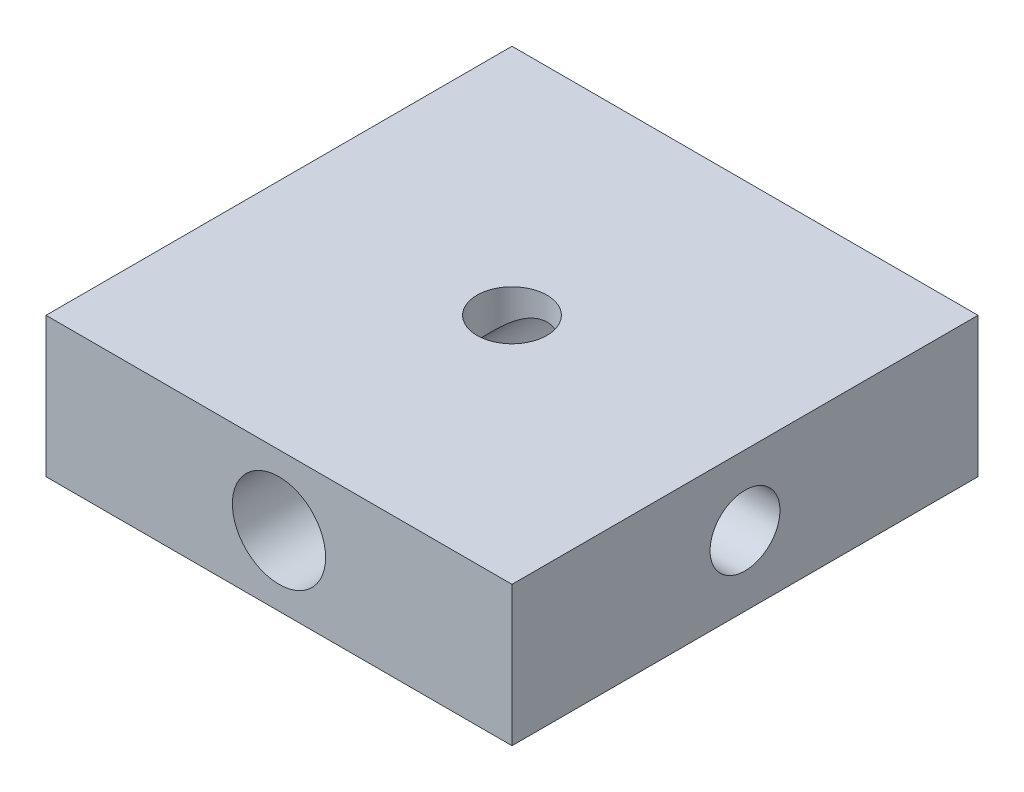
SolidWorks part; units mm, degrees
ref_plane "Front Plane" through (0, 0, 0) normal (0, 0, 1) x (1, 0, 0)
ref_plane "Top Plane" through (0, 0, 0) normal (0, 1, 0) x (1, 0, 0)
ref_plane "Right Plane" through (0, 0, 0) normal (1, 0, 0) x (0, 0, -1)
sketch "Sketch1" plane through (0, 0, 0) normal (0, 1, 0) x (1, 0, 0)
  line L1 (-10, -10) -> (10, -10)
  line L2 (-10, -10) -> (-10, 10)
  line L3 (-10, 10) -> (10, 10)
  line L4 (10, -10) -> (10, 10)
  line L5 (-10, -10) -> (10, 10) construction
  line L6 (-10, 10) -> (10, -10) construction
  point P0 (0, 0)
  dimension "D1" = 20
  dimension "D2" = 20
extrude "Boss-Extrude1" add sketch "Sketch1" along normal blind 6
sketch "Sketch2" plane through (0, 0, 10) normal (0, 0, 1) x (1, 0, 0)
  line L0 (-10, 3) -> (10, 3) construction
  line L1 (-10, 6) -> (-10, 0) construction
  line L2 (10, 6) -> (10, 0) construction
  line L3 (0, 6) -> (0, 0) construction
  line L4 (-10, 6) -> (10, 6) construction
  line L5 (-10, 0) -> (10, 0) construction
  circle A0 centre (0, 3) radius 2
  dimension "D1" = 4
extrude "Cut-Extrude1" cut sketch "Sketch2" against normal blind 20
sketch "Sketch3" plane through (0, 6, 0) normal (0, 1, 0) x (1, 0, 0)
  circle A0 centre (0, 0) radius 1.5
  dimension "D1" = 3
extrude "Cut-Extrude2" cut sketch "Sketch3" against normal blind 3
sketch "Sketch4" plane through (10, 0, 0) normal (1, 0, 0) x (0, 0, -1)
  line L0 (-10, 3) -> (10, 3) construction
  line L1 (-10, 6) -> (-10, 0) construction
  line L2 (10, 6) -> (10, 0) construction
  line L3 (0, 6) -> (0, 0) construction
  line L4 (-10, 6) -> (10, 6) construction
  circle A0 centre (0, 3) radius 1.5
  dimension "D1" = 3
extrude "Cut-Extrude3" cut sketch "Sketch4" against normal blind 9
sketch "Sketch5" plane through (-10, 0, 0) normal (-1, 0, 0) x (0, 0, 1)
  line L0 (-10, 3) -> (10, 3) construction
  line L1 (-10, 6) -> (-10, 0) construction
  line L2 (10, 6) -> (10, 0) construction
  line L3 (0, 6) -> (0, 0) construction
  line L4 (-10, 6) -> (10, 6) construction
  circle A0 centre (0, 3) radius 1
  dimension "D1" = 2
extrude "Cut-Extrude4" cut sketch "Sketch5" against normal blind 9
